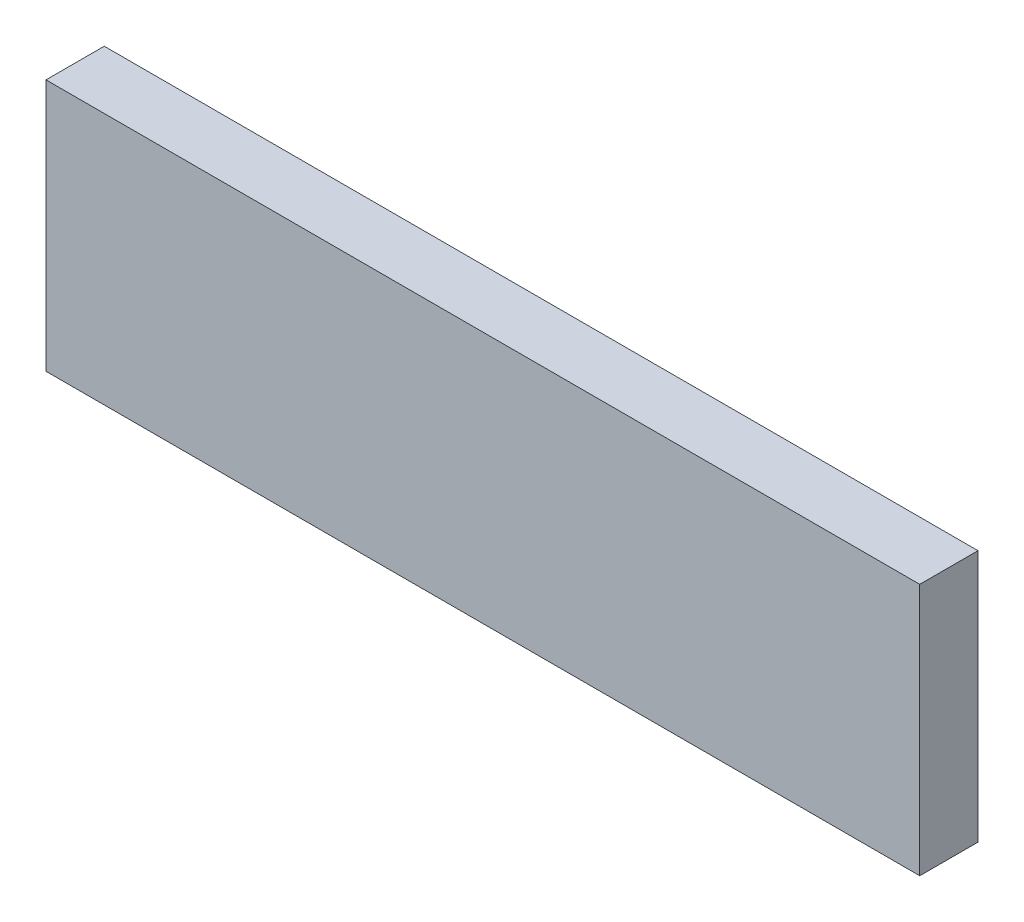
SolidWorks part; units mm, degrees
ref_plane "Front Plane" through (0, 0, 0) normal (0, 0, 1) x (1, 0, 0)
ref_plane "Top Plane" through (0, 0, 0) normal (0, 1, 0) x (1, 0, 0)
ref_plane "Right Plane" through (0, 0, 0) normal (1, 0, 0) x (0, 0, -1)
sketch "Sketch1" plane through (0, 0, 0) normal (0, 0, 1) x (1, 0, 0)
  line L1 (0, 0) -> (45, 0)
  line L2 (0, 0) -> (0, 13)
  line L3 (0, 13) -> (45, 13)
  line L4 (45, 0) -> (45, 13)
  dimension "D1" = 45
  dimension "D2" = 13
extrude "Boss-Extrude1" add sketch "Sketch1" along normal blind 3
